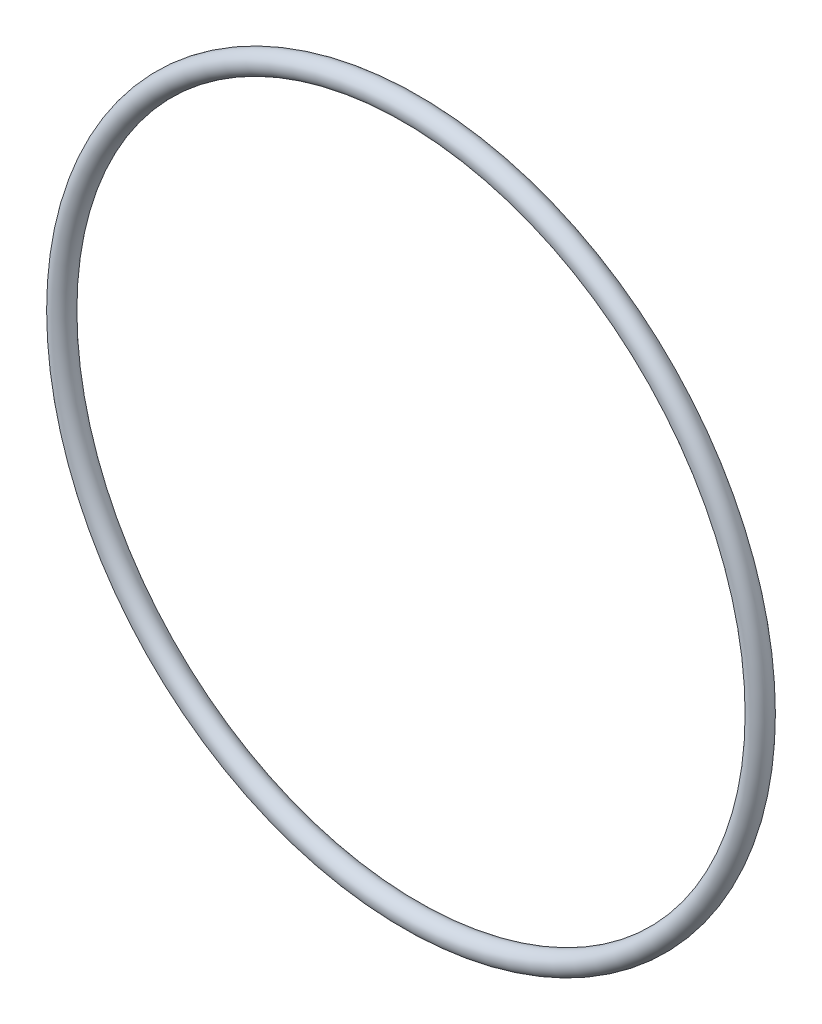
SolidWorks part; units mm, degrees
ref_plane "Płaszczyzna przednia" through (0, 0, 0) normal (0, 0, 1) x (1, 0, 0)
ref_plane "Płaszczyzna górna" through (0, 0, 0) normal (0, 1, 0) x (1, 0, 0)
ref_plane "Płaszczyzna prawa" through (0, 0, 0) normal (1, 0, 0) x (0, 0, -1)
sketch "Szkic1" plane through (0, 0, 0) normal (0, 0, 1) x (1, 0, 0)
  circle A0 centre (0, 0) radius 79
  dimension "D1" = 158
sketch "Szkic2" plane through (0, 0, 0) normal (0, 1, 0) x (1, 0, 0)
  circle A0 centre (-81.5, 0) radius 2.5
  dimension "D1" = 5
  dimension "D2" = 81.5
sweep "Wyciągnięcie po ścieżce1" add profiles "Szkic2" path "Szkic1"
